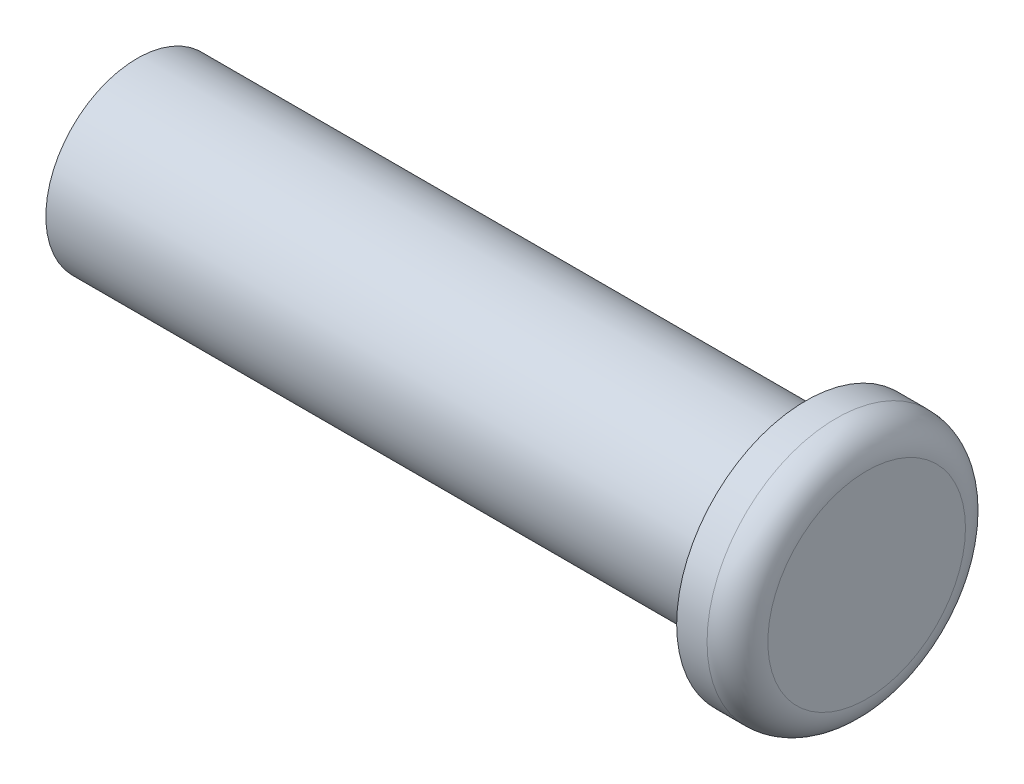
SolidWorks part; units mm, degrees
ref_plane "Front Plane" through (0, 0, 0) normal (0, 0, 1) x (1, 0, 0)
ref_plane "Top Plane" through (0, 0, 0) normal (0, 1, 0) x (1, 0, 0)
ref_plane "Right Plane" through (0, 0, 0) normal (1, 0, 0) x (0, 0, -1)
sketch "Sketch2" plane through (0, 0, 0) normal (1, 0, 0) x (0, 0, -1)
  circle A0 centre (0, 0) radius 3
  dimension "D1" = 6
extrude "Boss-Extrude1" add sketch "Sketch2" along normal mid plane 22
sketch "Sketch3" plane through (11, 0, 0) normal (1, 0, 0) x (0, 0, -1)
  circle A0 centre (0, 0) radius 4.25
  dimension "D1" = 8.5
extrude "Boss-Extrude2" add sketch "Sketch3" along normal blind 2
fillet "Fillet2" radius 1 1 edges at (13, 0, -4.25)
equation "\"D1@Boss-Extrude1\"= \"l_pin\""
equation "\"l_pin\"= 0.0220m"
